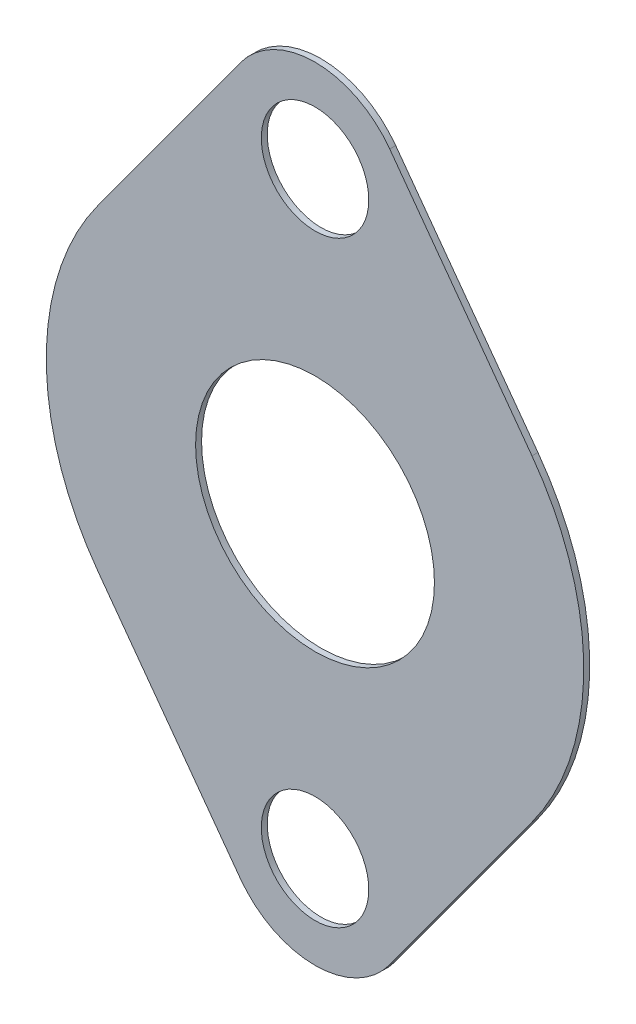
SolidWorks part; units mm, degrees
material "TESNIT BA-R"
ref_plane "Front Plane" through (0, 0, 0) normal (0, 0, 1) x (1, 0, 0)
ref_plane "Top Plane" through (0, 0, 0) normal (0, 1, 0) x (1, 0, 0)
ref_plane "Right Plane" through (0, 0, 0) normal (1, 0, 0) x (0, 0, -1)
sketch "Sketch1" plane through (0, 0, 0) normal (0, 0, 1) x (1, 0, 0)
  line L0 (-12.5148, 59.145) -> (-36.3331, 26.55)
  line L1 (-36.3331, -26.55) -> (-12.5148, -59.145)
  line L2 (12.5148, -59.145) -> (36.3331, -26.55)
  line L3 (36.3331, 26.55) -> (12.5148, 59.145)
  line L4 (0, 0) -> (66.5934, 0) construction
  line L5 (0, 0) -> (0, 74.5345) construction
  circle A0 centre (0, 0) radius 20
  arc A1 (-36.3331, 26.55) -> (-36.3331, -26.55) centre (0, 0) ccw
  arc A2 (-12.5148, -59.145) -> (12.5148, -59.145) centre (0, -50) ccw
  arc A3 (36.3331, -26.55) -> (36.3331, 26.55) centre (0, 0) ccw
  arc A4 (12.5148, 59.145) -> (-12.5148, 59.145) centre (0, 50) ccw
  circle A5 centre (0, -50) radius 9
  circle A6 centre (0, 50) radius 9
  dimension "D1" = 15.5
  dimension "D2" = 45
  dimension "D3" = 18
  dimension "D4" = 100
  dimension "D5" = 40
extrude "Extrude1" add sketch "Sketch1" along normal blind 1
